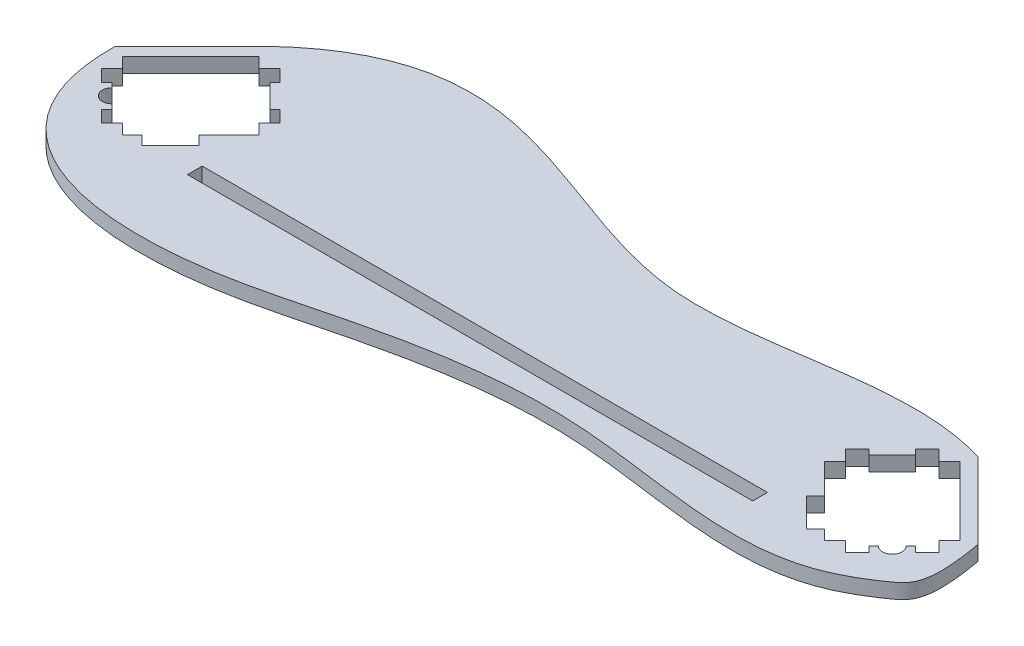
SolidWorks part; units mm, degrees
ref_plane "Front Plane" through (0, 0, 0) normal (0, 0, 1) x (1, 0, 0)
ref_plane "Top Plane" through (0, 0, 0) normal (0, 1, 0) x (1, 0, 0)
ref_plane "Right Plane" through (0, 0, 0) normal (1, 0, 0) x (0, 0, -1)
sketch "Sketch1" plane through (0, 0, 0) normal (0, 1, 0) x (1, 0, 0)
  line L0 (0.314, 0.4179) -> (0.314, 20.4179) construction
  line L1 (-57.5, 1.5) -> (57.5, 1.5)
  line L2 (-57.5, 1.5) -> (-57.5, -1.5)
  line L3 (-57.5, -1.5) -> (57.5, -1.5)
  line L4 (57.5, 1.5) -> (57.5, -1.5)
  line L5 (-57.5, 1.5) -> (57.5, -1.5) construction
  line L6 (-57.5, -1.5) -> (57.5, 1.5) construction
  line L7 (0.314, 12.788) -> (-57.186, 12.788) construction
  line L8 (-57.186, 12.788) -> (-59.3073, 14.9093)
  line L9 (-59.3073, 14.9093) -> (-57.1846, 17.0321)
  line L10 (-57.1846, 17.0321) -> (-59.5711, 19.4185)
  line L11 (-64.344, 24.1915) -> (-65.3708, 23.1648)
  line L12 (-60.5978, 18.3918) -> (-65.3708, 23.1648)
  line L13 (-62.9843, 20.7783) -> (-71.0099, 12.7526) construction
  line L14 (-57.186, 12.788) -> (-63.3322, 6.6418)
  line L15 (-63.3322, 6.6418) -> (-61.5085, 4.8182)
  line L16 (-59.5711, 19.4185) -> (-60.5978, 18.3918)
  line L17 (-66.7305, 26.578) -> (-64.344, 24.1915)
  line L18 (-68.8533, 24.4553) -> (-66.7305, 26.578)
  line L19 (-70.9746, 26.5766) -> (-68.8533, 24.4553)
  line L20 (-70.9746, 26.5766) -> (-84.9074, 12.6438)
  line L21 (-84.9074, 12.6438) -> (-82.7861, 10.5224)
  line L22 (-82.7861, 10.5224) -> (-84.9088, 8.3997)
  line L23 (-84.9088, 8.3997) -> (-82.5223, 6.0132)
  line L24 (-82.5223, 6.0132) -> (-81.4249, 7.1106)
  line L25 (-81.4249, 7.1106) -> (-76.6519, 2.3377)
  line L26 (-71.1188, -1.1448) -> (-73.2402, 0.9765)
  line L27 (-73.2402, 0.9765) -> (-75.3629, -1.1462)
  line L28 (-75.3629, -1.1462) -> (-77.7494, 1.2402)
  line L29 (-77.7494, 1.2402) -> (-76.6519, 2.3377)
  line L30 (-71.1188, -1.1448) -> (-69.1099, 0.8641)
  line L31 (-69.1099, 0.8641) -> (-67.2863, -0.9596)
  line L32 (-67.2863, -0.9596) -> (-61.5085, 4.8182)
  line L33 (69.7379, 0.8641) -> (67.9143, -0.9596)
  line L34 (71.7468, -1.1448) -> (69.7379, 0.8641)
  line L35 (71.7468, -1.1448) -> (73.8682, 0.9765)
  line L36 (73.8682, 0.9765) -> (75.9909, -1.1462)
  line L37 (75.9909, -1.1462) -> (78.3774, 1.2402)
  line L38 (78.3774, 1.2402) -> (77.2799, 2.3377)
  line L39 (82.0529, 7.1106) -> (77.2799, 2.3377)
  line L40 (83.1503, 6.0132) -> (82.0529, 7.1106)
  line L41 (85.5368, 8.3997) -> (83.1503, 6.0132)
  line L42 (83.4141, 10.5224) -> (85.5368, 8.3997)
  line L43 (85.5354, 12.6438) -> (83.4141, 10.5224)
  line L44 (71.6026, 26.5766) -> (85.5354, 12.6438)
  line L45 (71.6026, 26.5766) -> (69.4813, 24.4553)
  line L46 (69.4813, 24.4553) -> (67.3585, 26.578)
  line L47 (67.3585, 26.578) -> (64.972, 24.1915)
  line L48 (64.972, 24.1915) -> (65.9988, 23.1648)
  line L49 (61.2258, 18.3918) -> (65.9988, 23.1648)
  line L50 (60.1991, 19.4185) -> (61.2258, 18.3918)
  line L51 (57.8126, 17.0321) -> (60.1991, 19.4185)
  line L52 (59.9353, 14.9093) -> (57.8126, 17.0321)
  line L53 (57.814, 12.788) -> (59.9353, 14.9093)
  line L54 (57.814, 12.788) -> (63.9602, 6.6418)
  line L55 (63.9602, 6.6418) -> (62.1365, 4.8182)
  line L56 (67.9143, -0.9596) -> (62.1365, 4.8182)
  line L57 (-70.9746, 26.5766) -> (-72.0266, 29.1844) construction
  line L58 (-72.0266, 29.1844) -> (-87.4422, 13.7687)
  line L59 (72.6546, 29.1844) -> (88.0702, 13.7687)
  line L71 (0, 0) -> (0.314, 0.4179) construction
  circle A0 centre (-79.0384, 4.7242) radius 2
  circle A1 centre (79.6664, 4.7242) radius 2
  arc A4 (57.4077, 1.4976) -> (57.4094, 1.5) centre (46.32, 9.3749) ccw
  spline S0 degree 3 poles (-72.0266, 29.1844) (-42.481, 56.9922) (2.1619, 11.7671) (52.6693, 35.3671) (72.6546, 29.1844) knots 0 0 0 0 0.586494 1 1 1 1
  spline S1 degree 3 poles (-87.4422, 13.7687) (-88.0064, -16.6072) (-54.2812, -20.9892) (-5.5323, -8.0698) (24.1313, -2.3373) (67.2743, -13.1256) (85.8304, -2.055) (90.2703, 1.7113) (88.0702, 13.7687) knots 0 0 0 0 0.345715 0.403089 0.668585 0.888291 0.948309 1 1 1 1
  point P0 (0, 0)
  point P34 (-79.0384, 4.7242)
  dimension "D23" = 4
  dimension "D1" = 115
  dimension "D2" = 3
  dimension "D3" = 2.812
  dimension "D4" = 11.288
  dimension "D5" = 3
  dimension "D6" = 57.5
  dimension "D7" = 135
  dimension "D8" = 3.002
  dimension "D9" = 3.375
  dimension "D11" = 3.375
  dimension "D12" = 11.35
  dimension "D13" = 8.692
  dimension "D14" = 2.579
  dimension "D15" = 19.704
  dimension "D16" = 3
  dimension "D17" = 3.002
  dimension "D18" = 3.375
  dimension "D19" = 1.552
  dimension "D20" = 3.375
  dimension "D21" = 2.841
  dimension "D22" = 2.579
  dimension "D24" = 113.03
  dimension "D25" = 21.801
  dimension "D51" = 0.4179
extrude "Boss-Extrude1" add sketch "Sketch1" along normal blind 3 contours L58 S1 L59 S0 L39 A1 L38 L37 L36 L35 L34 L33 L56 L55 L54 L53 L52 L51 L50 L49 L48 L47 L46 L45 L44 L43 L42 L41 L40 L1 L4 L3 L2 A0 L25 L24 L23 L22 L21 L20 L19 L18 L17 L11 L12 L16
